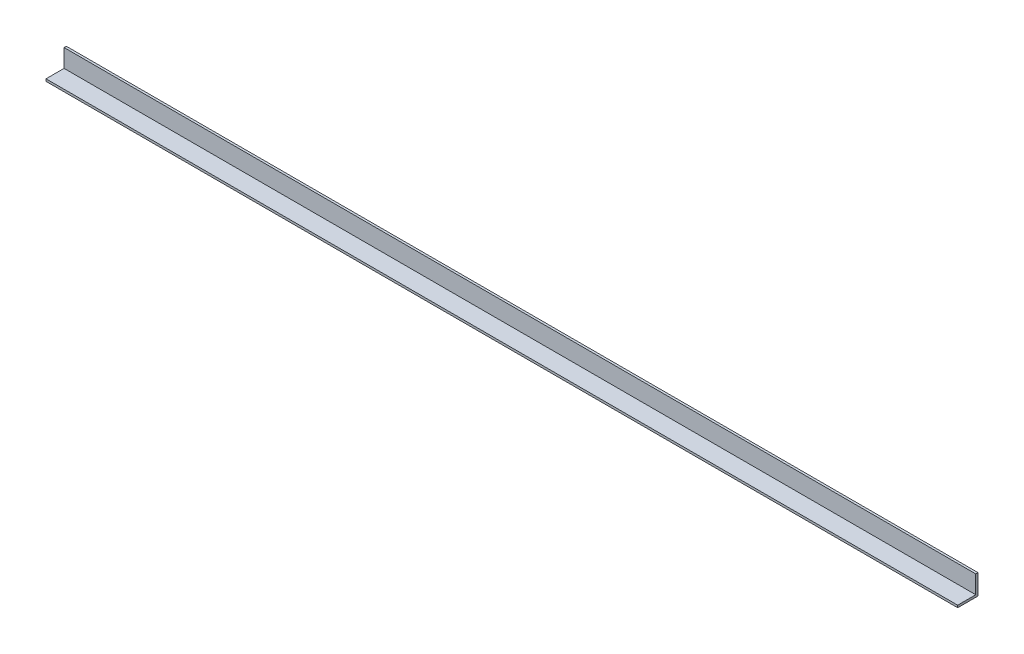
SolidWorks part; units mm, degrees
ref_plane "Front Plane" through (0, 0, 0) normal (0, 0, 1) x (1, 0, 0)
ref_plane "Top Plane" through (0, 0, 0) normal (0, 1, 0) x (1, 0, 0)
ref_plane "Right Plane" through (0, 0, 0) normal (1, 0, 0) x (0, 0, -1)
sketch "Sketch1" plane through (0, 0, 0) normal (0, 1, 0) x (1, 0, 0)
  line L1 (-505, 11.25) -> (505, 11.25)
  line L2 (-505, 11.25) -> (-505, -11.25)
  line L3 (-505, -11.25) -> (505, -11.25)
  line L4 (505, 11.25) -> (505, -11.25)
  line L5 (-505, 11.25) -> (505, -11.25) construction
  line L6 (-505, -11.25) -> (505, 11.25) construction
  point P0 (0, 0)
  dimension "D1" = 1010
  dimension "D2" = 22.5
extrude "Boss-Extrude1" add sketch "Sketch1" along normal blind 2.5
sketch "Sketch2" plane through (0, 2.5, 0) normal (0, 1, 0) x (1, 0, 0)
  line L0 (505, -11.25) -> (505, 11.25) construction
  line L1 (-505, 11.25) -> (505, 11.25)
  line L2 (-505, 11.25) -> (-505, 8.75)
  line L3 (-505, 8.75) -> (505, 8.75)
  line L4 (505, 11.25) -> (505, 8.75)
  dimension "D1" = 2.5
extrude "Boss-Extrude2" add sketch "Sketch2" along normal blind 20
